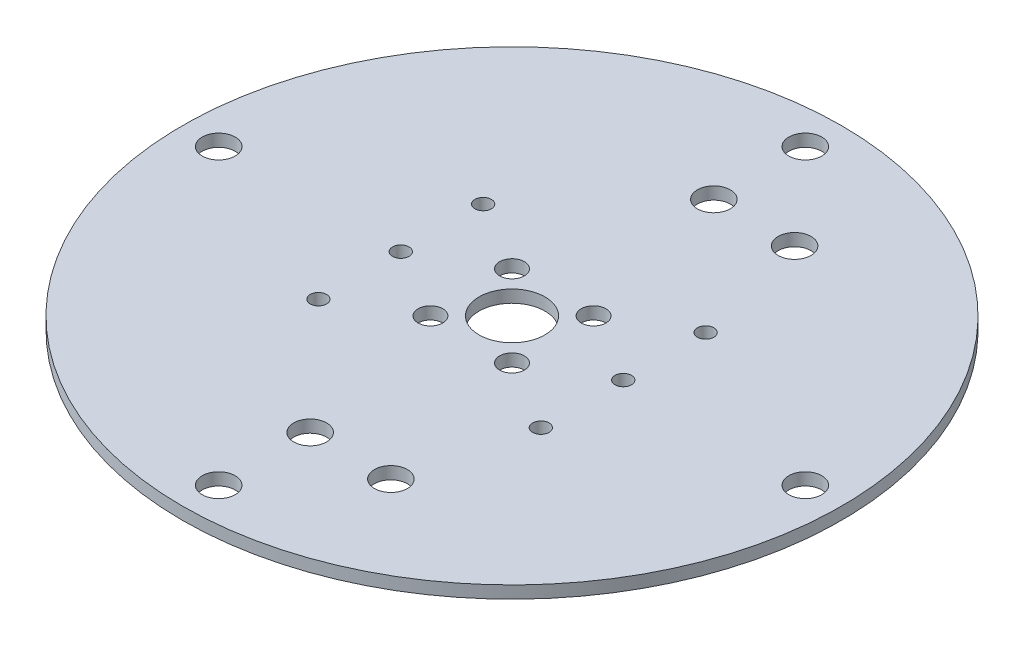
SolidWorks part; units mm, degrees
ref_plane "Front Plane" through (0, 0, 0) normal (0, 0, 1) x (1, 0, 0)
ref_plane "Top Plane" through (0, 0, 0) normal (0, 1, 0) x (1, 0, 0)
ref_plane "Right Plane" through (0, 0, 0) normal (1, 0, 0) x (0, 0, -1)
sketch "Sketch1" plane through (0, 0, 0) normal (0, 1, 0) x (1, 0, 0)
  line L0 (0, 40) -> (0, -40) construction
  line L1 (-40, 0) -> (40, 0) construction
  line L2 (0, 0) -> (-28.2843, 28.2843) construction
  line L3 (0, 0) -> (28.2843, 28.2843) construction
  line L4 (0, 0) -> (28.2843, -28.2843) construction
  line L5 (0, 0) -> (-28.2843, -28.2843) construction
  line L6 (0, 24.5) -> (9.8, 24.5) construction
  line L7 (0, 0) -> (-13.5, 0) construction
  line L8 (-13.5, 0) -> (-13.5, 10) construction
  line L9 (-13.5, 0) -> (-13.5, -10) construction
  circle A0 centre (0, 0) radius 40
  circle A1 centre (0, 0) radius 35.6 construction
  circle A2 centre (0, 35.6) radius 2
  circle A3 centre (-35.6, 0) radius 2
  circle A4 centre (0, -35.6) radius 2
  circle A5 centre (35.6, 0) radius 2
  circle A6 centre (0, 0) radius 4
  circle A7 centre (0, 0) radius 7 construction
  circle A8 centre (-4.9497, 4.9497) radius 1.5
  circle A9 centre (4.9497, 4.9497) radius 1.5
  circle A10 centre (4.9497, -4.9497) radius 1.5
  circle A11 centre (-4.9497, -4.9497) radius 1.5
  circle A12 centre (0, 0) radius 24.5 construction
  circle A13 centre (0, 24.5) radius 2
  circle A15 centre (0, -24.5) radius 2
  circle A17 centre (9.8, 24.5) radius 2
  circle A18 centre (9.8, -24.5) radius 2
  circle A19 centre (-13.5, 0) radius 1
  circle A20 centre (-13.5, 10) radius 1
  circle A21 centre (-13.5, -10) radius 1
  circle A22 centre (13.5, 10) radius 1
  circle A23 centre (13.5, 0) radius 1
  circle A24 centre (13.5, -10) radius 1
  dimension "D1" = 4.4
  dimension "D2" = 15.5
extrude "Boss-Extrude1" add sketch "Sketch1" along normal blind 1.5
